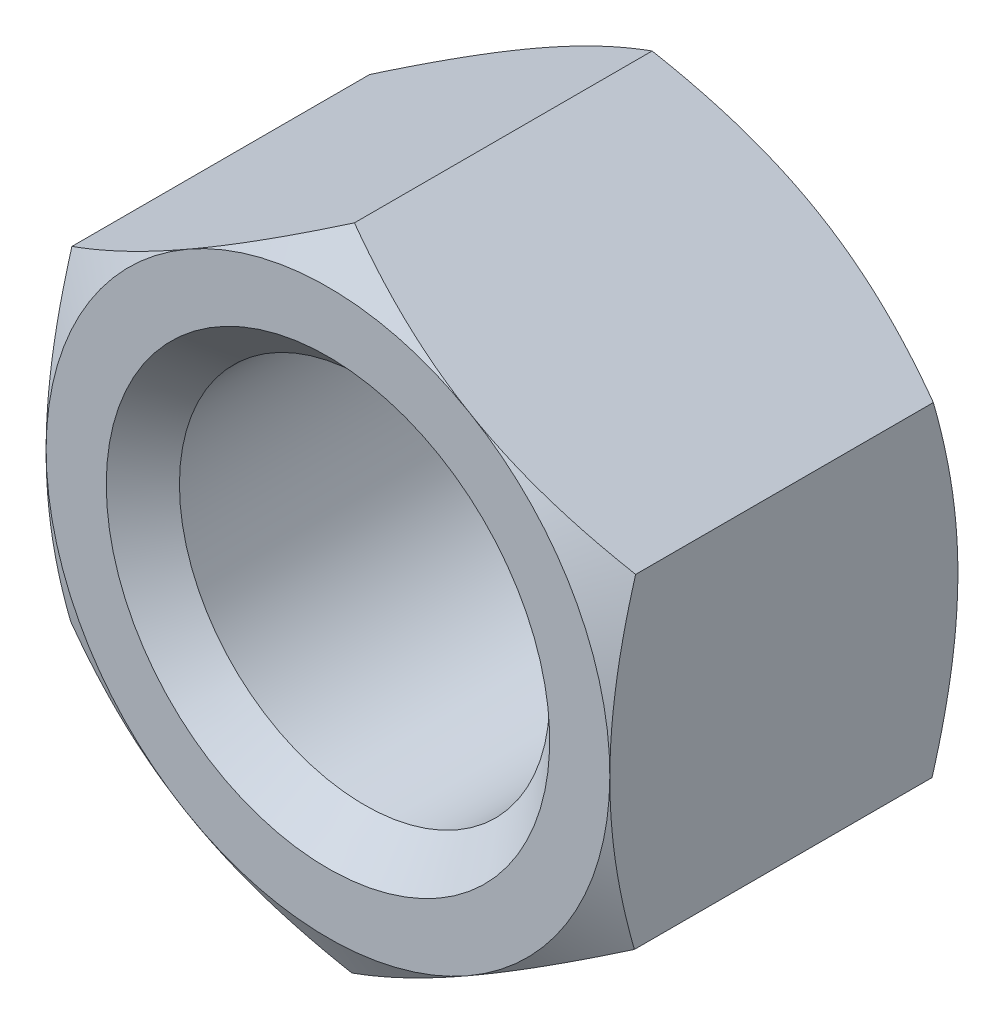
SolidWorks part; units mm, degrees
material "45"
ref_plane "基准面1" through (0, 0, 0) normal (0, 0, 1) x (1, 0, 0)
ref_plane "基准面2" through (0, 0, 0) normal (0, 1, 0) x (1, 0, 0)
ref_plane "基准面3" through (0, 0, 0) normal (1, 0, 0) x (0, 0, -1)
sketch "尺寸草图" plane through (0, 0, 0) normal (0, 0, 1) x (1, 0, 0)
  line L0 (0, 0) -> (31.6749, 0)
  line L1 (31.6749, 0) -> (37.4249, 0)
  line L2 (37.4249, 0) -> (44.3249, 0)
  line L3 (-4.7619, 0) -> (0, 0)
  point P3 (5, 0)
  point P4 (1.5, 0)
  point P5 (8.79, 0)
  point P6 (4.7, 0)
  point P7 (6.4, 0)
  point P8 (8, 0)
  dimension "D" = 5
  dimension "e" = 8.79
  dimension "P" = 1.5
  dimension "m" = 4.7
  dimension "mw" = 6.4
  dimension "s" = 8
  dimension "da" = 5.75
  dimension "dw" = 6.9
  dimension "D1" = 4.7619
sketch "草图1" plane through (0, 0, 0) normal (0, 0, 1) x (1, 0, 0)
  line L0 (-26.8088, 0) -> (37.1748, 0) construction
  line L1 (0, 25.0215) -> (0, -25.0215) construction
  line L3 (0.0173, 4.395) -> (-3.7975, 2.2125)
  line L4 (-3.7975, 2.2125) -> (-3.8148, -2.1825)
  line L5 (-3.8148, -2.1825) -> (-0.0173, -4.395)
  line L6 (-0.0173, -4.395) -> (3.7975, -2.2125)
  line L7 (3.7975, -2.2125) -> (3.8148, 2.1825)
  line L8 (3.8148, 2.1825) -> (0.0173, 4.395)
  circle A0 centre (0, 0) radius 3.8062 construction
  circle A1 centre (0, 0) radius 2.5
  dimension "D" = 5
  dimension "e" = 8.79
extrude "基体-拉伸" add sketch "草图1" along normal blind 4.7
cosmetic thread "装饰螺纹线1" parameters "D2"=5
sketch "草图2" plane through (0, 0, 0) normal (0, 0, -1) x (-1, 0, 0)
  line L0 (-3.8148, 2.1825) -> (-0.0173, 4.395) construction
  circle A0 centre (0, 0) radius 3.8062
  circle A1 centre (0, 0) radius 2.5 construction
extrude "切除-拉伸1" cut sketch "草图2" against normal through all draft 60 flip side to cut
sketch "草图3" plane through (0, 0, 4.7) normal (0, 0, 1) x (1, 0, 0)
  line L0 (0.0173, 4.395) -> (-3.7975, 2.2125) construction
  circle A0 centre (0, 0) radius 3.8062
extrude "切除-拉伸2" cut sketch "草图3" against normal through all draft 60 flip side to cut
chamfer "倒角1" distance 0.494 angle 45 2 edges at (2.5, 0, 0) (2.5, 0, 4.7)
equation "\"e@草图1\" = \"e@尺寸草图\""
equation "\"D1@尺寸草图\" = \"D@尺寸草图\" / 1.05"
equation "\"D@草图1\" = \"D@尺寸草图\""
equation "\"m@基体-拉伸\" = \"m@尺寸草图\""
equation "\"D2@装饰螺纹线1\" = \"D@尺寸草图\""
equation "\"D1@倒角1\" =  ( \"da@尺寸草图\" - \"D1@尺寸草图\" )  / 2"
